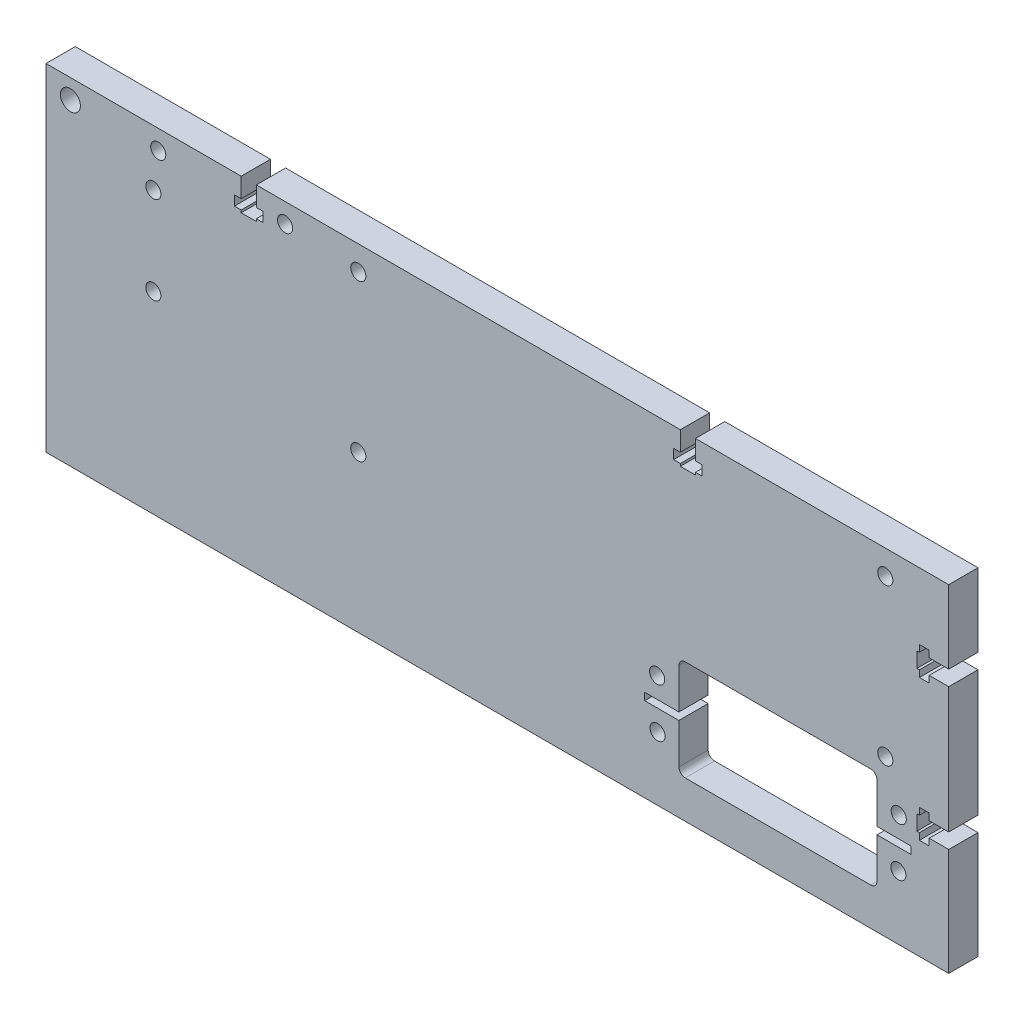
SolidWorks part; units mm, degrees
ref_plane "Płaszczyzna przednia" through (0, 0, 0) normal (0, 0, 1) x (1, 0, 0)
ref_plane "Płaszczyzna górna" through (0, 0, 0) normal (0, 1, 0) x (1, 0, 0)
ref_plane "Płaszczyzna prawa" through (0, 0, 0) normal (1, 0, 0) x (0, 0, -1)
sketch "Szkic1" plane through (0, 0, 0) normal (0, 0, 1) x (1, 0, 0)
  line L0 (-175.3, 32.1843) -> (-175.3, 101.1843)
  line L1 (-175.3, 32.1843) -> (9.7, 32.1843)
  line L2 (-175.3, 101.1843) -> (9.7, 101.1843)
  line L3 (9.7, 32.1843) -> (9.7, 101.1843)
  dimension "D1" = 185
  dimension "D2" = 69
extrude "Dodanie-wyciągnięcie1" add sketch "Szkic1" against normal blind 6
sketch "Szkic6" plane through (0, 0, -6) normal (0, 0, -1) x (-1, 0, 0)
  line L0 (135.3, 101.1843) -> (132.2, 101.1843)
  line L1 (135.3, 101.1843) -> (135.3, 97.1843)
  line L2 (132.2, 101.1843) -> (132.2, 97.1843)
  line L3 (135.3, 94.6843) -> (132.2, 94.6843)
  line L4 (169.3, 101.1843) -> (-9.7, 101.1843) construction
  line L5 (136.675, 97.1843) -> (136.675, 95.1843)
  line L6 (136.675, 97.1843) -> (135.3, 97.1843)
  line L7 (136.675, 95.1843) -> (135.3, 95.1843)
  line L8 (130.825, 97.1843) -> (130.825, 95.1843)
  line L9 (132.2, 97.1843) -> (130.825, 97.1843)
  line L10 (132.2, 95.1843) -> (130.825, 95.1843)
  line L11 (135.3, 95.1843) -> (135.3, 94.6843)
  line L12 (132.2, 95.1843) -> (132.2, 94.6843)
  line L13 (175.3, 101.1843) -> (175.3, 32.1843) construction
  dimension "D1" = 6.5
  dimension "D2" = 5.85
  dimension "D3" = 3.1
  dimension "D4" = 1.375
  dimension "D5" = 2
  dimension "D6" = 0.5
  dimension "D7" = 40
extrude "Wytnij-wyciągnięcie2" cut sketch "Szkic6" against normal through all
pattern_linear "Szyk liniowy1" count 2 spacing 90 along (1, 0, 0) of "Wytnij-wyciągnięcie2"
sketch "Szkic7" plane through (0, 0, -6) normal (0, 0, -1) x (-1, 0, 0)
  line L0 (-9.7, 86.1843) -> (-9.7, 83.0843)
  line L1 (-9.7, 86.1843) -> (-5.7, 86.1843)
  line L2 (-9.7, 83.0843) -> (-5.7, 83.0843)
  line L3 (-3.2, 86.1843) -> (-3.2, 83.0843)
  line L4 (-9.7, 32.1843) -> (-9.7, 101.1843) construction
  line L5 (-3.7, 87.5593) -> (-5.7, 87.5593)
  line L6 (-3.7, 87.5593) -> (-3.7, 86.1843)
  line L7 (-5.7, 87.5593) -> (-5.7, 86.1843)
  line L8 (-3.7, 81.7093) -> (-5.7, 81.7093)
  line L9 (-3.7, 83.0843) -> (-3.7, 81.7093)
  line L10 (-3.7, 83.0843) -> (-3.2, 83.0843)
  line L11 (-3.7, 86.1843) -> (-3.2, 86.1843)
  line L12 (-5.7, 83.0843) -> (-5.7, 81.7093)
  line L13 (-9.7, 101.1843) -> (42.2, 101.1843) construction
  dimension "D1" = 3.1
  dimension "D2" = 2
  dimension "D3" = 5.85
  dimension "D4" = 1.375
  dimension "D5" = 0.5
  dimension "D6" = 6.5
  dimension "D7" = 15
extrude "Wytnij-wyciągnięcie3" cut sketch "Szkic7" against normal through all
pattern_linear "Szyk liniowy2" count 2 spacing 28.9 along (0, -1, 0) of "Wytnij-wyciągnięcie3"
sketch "Szkic8" plane through (0, 0, -6) normal (0, 0, -1) x (-1, 0, 0)
  circle A4 centre (111.3, 96.1843) radius 1.55 construction
  circle A5 centre (111.3, 64.1843) radius 1.55 construction
  circle A6 centre (3.3, 64.1843) radius 1.55 construction
  circle A7 centre (3.3, 96.1843) radius 1.55 construction
  circle A8 centre (111.3, 96.1843) radius 1.55
  circle A9 centre (111.3, 64.1843) radius 1.55
  circle A10 centre (3.3, 64.1843) radius 1.55
  circle A11 centre (3.3, 96.1843) radius 1.55
extrude "Wytnij-wyciągnięcie4" cut sketch "Szkic8" against normal through all
sketch "Szkic11" plane through (0, 0, -6) normal (0, 0, -1) x (-1, 0, 0)
  line L0 (135.3, 101.1843) -> (175.3, 101.1843) construction
  line L1 (175.3, 101.1843) -> (175.3, 32.1843) construction
  circle A0 centre (170.3, 97.1843) radius 2.05
  circle A2 centre (152.3, 97.1843) radius 1.55
  circle A3 centre (126.3, 97.1843) radius 1.55
  dimension "D1" = 4.1
  dimension "D2" = 0
  dimension "D3" = 3.1
  dimension "D4" = 3.1
  dimension "D5" = 26
  dimension "D6" = 18
  dimension "D7" = 4
  dimension "D8" = 0
  dimension "D9" = 5
extrude "Wytnij-wyciągnięcie7" cut sketch "Szkic11" against normal blind 10
sketch "Szkic12" plane through (0, 0, -6) normal (0, 0, -1) x (-1, 0, 0)
  line L1 (6.3, 40.1843) -> (44.3, 40.1843) construction
  line L2 (44.3, 60.1843) -> (6.3, 60.1843) construction
  line L3 (45.3, 41.1843) -> (45.3, 59.1843) construction
  line L4 (5.3, 59.1843) -> (5.3, 41.1843)
  line L5 (6.3, 40.1843) -> (44.3, 40.1843)
  line L6 (5, 59.1843) -> (5, 41.1843)
  line L7 (45.3, 41.1843) -> (45.3, 59.1843)
  line L8 (5.3, 59.1843) -> (5.3, 41.1843) construction
  line L9 (5, 59.1843) -> (5, 41.1843) construction
  line L10 (6.3, 60.1843) -> (44.3, 60.1843)
  line L11 (45.3, 41.1843) -> (45.3, 59.1843) construction
  line L12 (6.3, 39.8843) -> (44.3, 39.8843)
  line L13 (45.6, 41.1843) -> (45.6, 59.1843)
  line L15 (6.3, 60.4843) -> (44.3, 60.4843)
  line L17 (5.3, 59.1843) -> (5.3, 60.1843) construction
  line L18 (5.3, 60.1843) -> (45.3, 60.1843) construction
  line L19 (5, 60.4843) -> (45.6, 60.4843) construction
  line L20 (5, 59.1843) -> (5, 60.4843) construction
  line L21 (45.3, 60.1843) -> (45.3, 59.1843) construction
  line L22 (45.6, 60.4843) -> (45.6, 59.1843) construction
  line L24 (45.6, 41.1843) -> (45.6, 59.1843) construction
  arc A0 (44.3, 40.1843) -> (45.3, 41.1843) centre (44.3, 41.1843) ccw construction
  arc A1 (6.3, 60.1843) -> (5.3, 59.1843) centre (6.3, 59.1843) ccw
  arc A3 (5.3, 41.1843) -> (6.3, 40.1843) centre (6.3, 41.1843) ccw construction
  arc A4 (44.3, 40.1843) -> (45.3, 41.1843) centre (44.3, 41.1843) ccw
  arc A5 (5, 41.1843) -> (6.3, 39.8843) centre (6.3, 41.1843) ccw
  arc A6 (44.3, 39.8843) -> (45.6, 41.1843) centre (44.3, 41.1843) ccw
  arc A7 (5.3, 41.1843) -> (6.3, 40.1843) centre (6.3, 41.1843) ccw
  arc A8 (-1.5794, 43.8408) -> (-1.5794, 46.5352) centre (0.623, 45.188) ccw construction
  arc A9 (-1.5804, 53.8599) -> (-1.5804, 56.5087) centre (0.54, 55.1843) ccw construction
  arc A10 (52.1794, 46.5352) -> (52.1794, 43.8408) centre (49.977, 45.188) ccw construction
  arc A11 (52.1804, 56.5087) -> (52.1804, 53.8599) centre (50.06, 55.1843) ccw construction
  arc A12 (-1.5794, 43.8408) -> (-1.5794, 46.5352) centre (0.623, 45.188) ccw
  arc A13 (-1.5804, 53.8599) -> (-1.5804, 56.5087) centre (0.54, 55.1843) ccw
  arc A14 (52.1794, 46.5352) -> (52.1794, 43.8408) centre (49.977, 45.188) ccw
  arc A15 (52.1804, 56.5087) -> (52.1804, 53.8599) centre (50.06, 55.1843) ccw
  circle A16 centre (49.977, 45.188) radius 1.55
  circle A17 centre (50.06, 55.1843) radius 1.55
  circle A18 centre (0.54, 55.1843) radius 1.55
  circle A19 centre (0.623, 45.188) radius 1.55
  arc A20 (45.3, 59.1843) -> (44.3, 60.1843) centre (44.3, 59.1843) ccw
  arc A22 (5, 59.1843) -> (6.3, 60.4843) centre (6.3, 59.1843) cw
  arc A23 (45.6, 59.1843) -> (44.3, 60.4843) centre (44.3, 59.1843) ccw
  dimension "D2" = 3.1
  dimension "D3" = 3.1
  dimension "D4" = 3.1
  dimension "D5" = 3.1
  dimension "D7" = 1
  dimension "D8" = 1.3
  dimension "D9" = 1
  dimension "D10" = 1.3
  dimension "D6" = 0
  dimension "D1" = 0.3
sketch "Szkic13" plane through (0, 0, -6) normal (0, 0, -1) x (-1, 0, 0)
  line L0 (6.3, 39.8843) -> (44.3, 39.8843) construction
  line L1 (45.6, 41.1843) -> (45.6, 59.1843) construction
  line L5 (5, 59.1843) -> (5, 41.1843) construction
  line L6 (6.3, 39.8843) -> (44.3, 39.8843)
  line L7 (45.6, 41.1843) -> (45.6, 59.1843)
  line L9 (6.3, 60.4843) -> (44.3, 60.4843) construction
  line L11 (5, 59.1843) -> (5, 41.1843)
  line L13 (6.3, 60.4843) -> (44.3, 60.4843)
  arc A0 (44.3, 39.8843) -> (45.6, 41.1843) centre (44.3, 41.1843) ccw construction
  arc A1 (5, 41.1843) -> (6.3, 39.8843) centre (6.3, 41.1843) ccw construction
  arc A2 (44.3, 39.8843) -> (45.6, 41.1843) centre (44.3, 41.1843) ccw
  arc A3 (5, 41.1843) -> (6.3, 39.8843) centre (6.3, 41.1843) ccw
  circle A4 centre (49.977, 45.188) radius 1.55 construction
  circle A5 centre (50.06, 55.1843) radius 1.55 construction
  circle A6 centre (0.54, 55.1843) radius 1.55 construction
  circle A7 centre (0.623, 45.188) radius 1.55 construction
  circle A8 centre (49.977, 45.188) radius 1.55
  circle A9 centre (50.06, 55.1843) radius 1.55
  circle A10 centre (0.54, 55.1843) radius 1.55
  circle A11 centre (0.623, 45.188) radius 1.55
  arc A14 (45.6, 59.1843) -> (44.3, 60.4843) centre (44.3, 59.1843) ccw construction
  arc A15 (6.3, 60.4843) -> (5, 59.1843) centre (6.3, 59.1843) ccw construction
  arc A16 (45.6, 59.1843) -> (44.3, 60.4843) centre (44.3, 59.1843) ccw
  arc A17 (6.3, 60.4843) -> (5, 59.1843) centre (6.3, 59.1843) ccw
extrude "Wytnij-wyciągnięcie8" cut sketch "Szkic13" against normal blind 6
sketch "Szkic14" plane through (0, 0, -6) normal (0, 0, -1) x (-1, 0, 0)
  line L0 (45.6, 50.9343) -> (45.6, 49.4343)
  line L3 (45.6, 49.4343) -> (52.6, 49.4343)
  line L5 (52.6, 49.4343) -> (52.6, 50.9343)
  line L6 (6.3, 39.8843) -> (44.3, 39.8843) construction
  line L7 (52.6, 50.9343) -> (45.6, 50.9343)
  line L9 (5, 50.9343) -> (5, 49.4343)
  line L10 (5, 50.9343) -> (-2, 50.9343)
  line L11 (5, 49.4343) -> (-2, 49.4343)
  line L12 (45.6, 41.1843) -> (45.6, 59.1843) construction
  line L13 (-2, 50.9343) -> (-2, 49.4343)
  line L14 (5, 59.1843) -> (5, 41.1843) construction
  point P2 (51.6, 51.7343)
  dimension "D1" = 1.5
  dimension "D2" = 9.55
  dimension "D3" = 7
  dimension "D4" = 7
  dimension "D5" = 1.5
  dimension "D6" = 9.55
extrude "Wytnij-wyciągnięcie9" cut sketch "Szkic14" against normal blind 10
sketch "Szkic15" plane through (0, 0, -6) normal (0, 0, -1) x (-1, 0, 0)
  line L0 (150.3, 91.2843) -> (156.3, 91.2843) construction
  line L1 (150.3, 88.1843) -> (156.3, 88.1843) construction
  line L2 (150.3, 73.2843) -> (156.3, 73.2843) construction
  line L3 (150.3, 70.1843) -> (156.3, 70.1843) construction
  line L4 (150.3, 91.2843) -> (156.3, 91.2843)
  line L5 (150.3, 88.1843) -> (156.3, 88.1843)
  line L6 (150.3, 73.2843) -> (156.3, 73.2843)
  line L7 (150.3, 70.1843) -> (156.3, 70.1843)
  line L8 (153.3, 91.2843) -> (153.3, 88.1843)
  line L9 (153.3, 73.2843) -> (153.3, 70.1843)
  circle A0 centre (153.3, 89.7343) radius 1.55
  circle A1 centre (153.3, 71.7343) radius 1.55
sketch "Szkic16" plane through (0, 0, -6) normal (0, 0, -1) x (-1, 0, 0)
  circle A0 centre (153.3, 89.7343) radius 1.55 construction
  circle A1 centre (153.3, 71.7343) radius 1.55 construction
  circle A2 centre (153.3, 89.7343) radius 1.55
  circle A3 centre (153.3, 71.7343) radius 1.55
extrude "Wytnij-wyciągnięcie10" cut sketch "Szkic16" against normal blind 6
equation "\"tolerancja_wpusy\"=0.2"
equation "\"dlugosc_wpustu_duzy\"=20"
equation "\"srednica_otworu_M3\"=3.1"
equation "\"szerokosc_nogi_T\"=3.1"
equation "\"dlugosc_T_30\"=11"
equation "\"grubosc_na_nakretke_kwadrat\"=2"
equation "\"szerokosc_na_nakretke_kwadrat\"=5.85"
equation "\"wyokosc_nadstawki_T\"=0.5"
equation "\"dlugosc_T_15_6\"=11"
equation "\"dlugosc_T_20_6\"=14"
equation "\"D2@Szkic6\" = \"szerokosc_na_nakretke_kwadrat\""
equation "\"D3@Szkic6\"=\"szerokosc_nogi_T\""
equation "\"D4@Szkic6\"=(\"szerokosc_na_nakretke_kwadrat\"-\"szerokosc_nogi_T\")/2"
equation "\"D5@Szkic6\"=\"grubosc_na_nakretke_kwadrat\""
equation "\"D6@Szkic6\"=\"wyokosc_nadstawki_T\""
equation "\"D1@Szkic7\"=\"szerokosc_nogi_T\""
equation "\"D2@Szkic7\"=\"grubosc_na_nakretke_kwadrat\""
equation "\"D3@Szkic7\"=\"szerokosc_na_nakretke_kwadrat\""
equation "\"D4@Szkic7\"=(\"szerokosc_na_nakretke_kwadrat\"-\"szerokosc_nogi_T\")/2"
equation "\"D5@Szkic7\"=\"wyokosc_nadstawki_T\""
equation "\"D3@Szkic11\"=\"srednica_otworu_M3\""
equation "\"D4@Szkic11\"=\"srednica_otworu_M3\""
equation "\"D2@Szkic12\"=\"srednica_otworu_M3\""
equation "\"D3@Szkic12\"=\"srednica_otworu_M3\""
equation "\"D4@Szkic12\"=\"srednica_otworu_M3\""
equation "\"D5@Szkic12\"=\"srednica_otworu_M3\""
